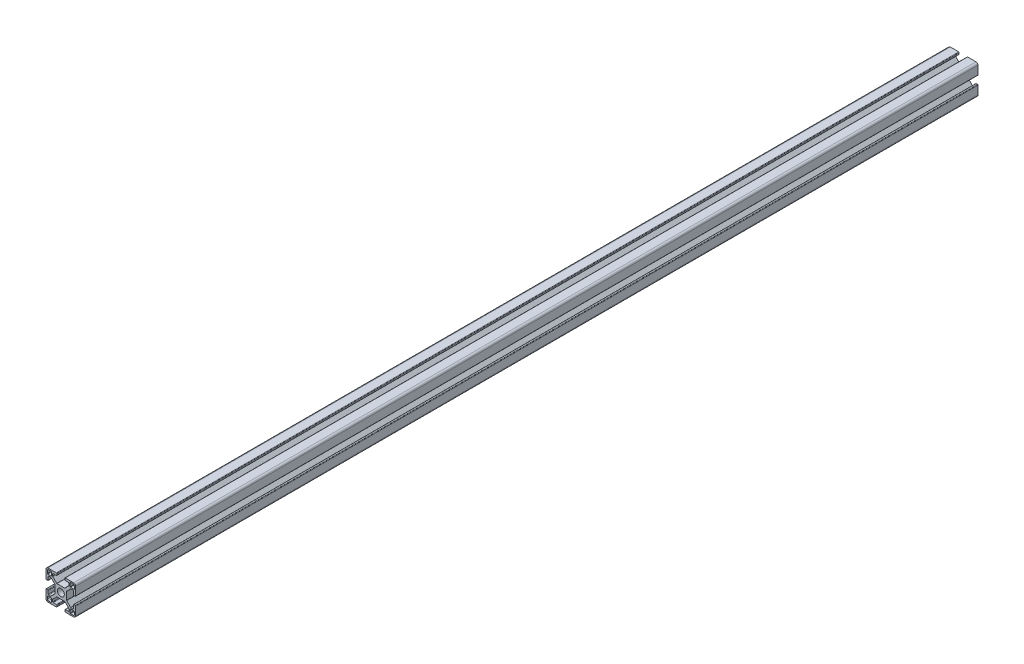
SolidWorks part; units mm, degrees
ref_plane "Front Plane" through (0, 0, 0) normal (0, 0, 1) x (1, 0, 0)
ref_plane "Top Plane" through (0, 0, 0) normal (0, 1, 0) x (1, 0, 0)
ref_plane "Right Plane" through (0, 0, 0) normal (1, 0, 0) x (0, 0, -1)
sketch "Sketch1" plane through (0, 0, 0) normal (0, 0, 1) x (1, 0, 0)
  line L0 (3.9799, -2.4733) -> (3.1981, -1.4942) construction
  line L1 (1.4942, -3.1981) -> (2.4733, -3.9799) construction
  line L2 (-2.4733, -3.9799) -> (-1.4942, -3.1981) construction
  line L3 (-3.1981, -1.4942) -> (-3.9799, -2.4733) construction
  line L4 (-3.9799, 2.4733) -> (-3.1981, 1.4942) construction
  line L5 (-1.4942, 3.1981) -> (-2.4733, 3.9799) construction
  line L6 (2.4733, 3.9799) -> (1.4942, 3.1981) construction
  line L7 (3.1981, 1.4942) -> (3.9799, 2.4733) construction
  line L8 (-12.6999, -13.6999) -> (-9.881, -13.6999)
  line L9 (-13.6999, -9.881) -> (-13.6999, -12.6999)
  line L10 (-9.88, -9.5) -> (-13.3189, -9.5)
  line L11 (-9.5, -13.3189) -> (-9.5, -9.88)
  line L12 (13.6999, -12.6999) -> (13.6999, -9.881)
  line L13 (9.881, -13.6999) -> (12.6999, -13.6999)
  line L14 (9.5, -9.88) -> (9.5, -13.3189)
  line L15 (13.3189, -9.5) -> (9.88, -9.5)
  line L16 (9.88, 9.5) -> (13.3189, 9.5)
  line L17 (9.5, 13.3189) -> (9.5, 9.88)
  line L18 (12.6999, 13.6999) -> (9.881, 13.6999)
  line L19 (13.6999, 9.881) -> (13.6999, 12.6999)
  line L20 (-13.6999, 12.6999) -> (-13.6999, 9.881)
  line L21 (-9.881, 13.6999) -> (-12.6999, 13.6999)
  line L22 (-9.5, 9.88) -> (-9.5, 13.3189)
  line L23 (-13.3189, 9.5) -> (-9.88, 9.5)
  line L24 (14.4999, -4) -> (13.2425, -4)
  line L25 (12.7425, -4.5) -> (12.7425, -7.7325)
  line L26 (12.2428, -8.25) -> (10.2602, -8.25)
  line L27 (9.9066, -8.1035) -> (5.9811, -4.178)
  line L28 (5.8347, -3.8245) -> (5.8347, -1.0125)
  line L29 (5.8347, -1.0125) -> (5.3247, -0.0625) construction
  line L30 (5.3247, -0.0625) -> (5.8347, 0.8875) construction
  line L31 (5.8347, 0.8875) -> (5.8347, 3.8245)
  line L32 (5.9811, 4.178) -> (9.9066, 8.1035)
  line L33 (10.2602, 8.25) -> (12.2428, 8.25)
  line L34 (12.7425, 7.7325) -> (12.7425, 4.5)
  line L35 (13.2425, 4) -> (14.4999, 4)
  line L36 (14.9999, 4.5) -> (14.9999, 12.9999)
  line L37 (12.9999, 14.9999) -> (4.5, 14.9999)
  line L38 (4, 14.4999) -> (4, 13.2425)
  line L39 (4.5, 12.7425) -> (7.7325, 12.7425)
  line L40 (8.25, 12.2428) -> (8.25, 10.2602)
  line L41 (8.1035, 9.9066) -> (4.178, 5.9811)
  line L42 (3.8245, 5.8347) -> (0.95, 5.8347)
  line L43 (0.95, 5.8347) -> (0, 5.3247) construction
  line L44 (0, 5.3247) -> (-0.95, 5.8347) construction
  line L45 (-0.95, 5.8347) -> (-3.8245, 5.8347)
  line L46 (-4.178, 5.9811) -> (-8.1035, 9.9066)
  line L47 (-8.25, 10.2602) -> (-8.25, 12.2428)
  line L48 (-7.7325, 12.7425) -> (-4.5, 12.7425)
  line L49 (-4, 13.2425) -> (-4, 14.4999)
  line L50 (-4.5, 14.9999) -> (-12.9999, 14.9999)
  line L51 (-14.9999, 12.9999) -> (-14.9999, 4.5)
  line L52 (-14.4999, 4) -> (-13.2425, 4)
  line L53 (-12.7425, 4.5) -> (-12.7425, 7.7325)
  line L54 (-12.2428, 8.25) -> (-10.2602, 8.25)
  line L55 (-9.9066, 8.1035) -> (-5.9811, 4.178)
  line L56 (-5.8347, 3.8245) -> (-5.8347, 0.8875)
  line L57 (-5.8347, 0.8875) -> (-5.3247, -0.0625) construction
  line L58 (-5.3247, -0.0625) -> (-5.8347, -1.0125) construction
  line L59 (-5.8347, -1.0125) -> (-5.8347, -3.8245)
  line L60 (-5.9811, -4.178) -> (-9.9066, -8.1035)
  line L61 (-10.2602, -8.25) -> (-12.2428, -8.25)
  line L62 (-12.7425, -7.7325) -> (-12.7425, -4.5)
  line L63 (-13.2425, -4) -> (-14.4999, -4)
  line L64 (-14.9999, -4.5) -> (-14.9999, -12.9999)
  line L65 (-12.9999, -14.9999) -> (-4.5, -14.9999)
  line L66 (-4, -14.4999) -> (-4, -13.2425)
  line L67 (-4.5, -12.7425) -> (-7.7325, -12.7425)
  line L68 (-8.25, -12.2428) -> (-8.25, -10.2602)
  line L69 (-8.1035, -9.9066) -> (-4.178, -5.9811)
  line L70 (-3.8245, -5.8347) -> (-0.95, -5.8347)
  line L71 (-0.95, -5.8347) -> (0, -5.3247) construction
  line L72 (0, -5.3247) -> (0.95, -5.8347) construction
  line L73 (0.95, -5.8347) -> (3.8245, -5.8347)
  line L74 (4.178, -5.9811) -> (8.1035, -9.9066)
  line L75 (8.25, -10.2602) -> (8.25, -12.2428)
  line L76 (7.7325, -12.7425) -> (4.5, -12.7425)
  line L77 (4, -13.2425) -> (4, -14.4999)
  line L78 (4.5, -14.9999) -> (12.9999, -14.9999)
  line L79 (14.9999, -12.9999) -> (14.9999, -4.5)
  line L80 (-5.8347, -1.0125) -> (-5.8347, 0.8875)
  line L81 (-0.95, 5.8347) -> (0.95, 5.8347)
  line L82 (5.8347, 0.8875) -> (5.8347, -1.0125)
  line L83 (-0.95, -5.8347) -> (0.95, -5.8347)
  arc A0 (2.4733, -3.9799) -> (3.9799, -2.4733) centre (3.1422, -3.1422) ccw construction
  arc A1 (-1.4942, -3.1981) -> (1.4942, -3.1981) centre (0, 0) ccw construction
  arc A2 (-3.9799, -2.4733) -> (-2.4733, -3.9799) centre (-3.1422, -3.1422) ccw construction
  arc A3 (-3.1981, 1.4942) -> (-3.1981, -1.4942) centre (0, 0) ccw construction
  arc A4 (-2.4733, 3.9799) -> (-3.9799, 2.4733) centre (-3.1422, 3.1422) ccw construction
  arc A5 (1.4942, 3.1981) -> (-1.4942, 3.1981) centre (0, 0) ccw construction
  arc A6 (3.9799, 2.4733) -> (2.4733, 3.9799) centre (3.1422, 3.1422) ccw construction
  arc A7 (3.1981, -1.4942) -> (3.1981, 1.4942) centre (0, 0) ccw construction
  arc A8 (-13.6999, -12.6999) -> (-12.6999, -13.6999) centre (-12.6999, -12.6999) ccw
  arc A9 (-13.3189, -9.5) -> (-13.6999, -9.881) centre (-13.3189, -9.881) ccw
  arc A10 (-9.5, -9.88) -> (-9.88, -9.5) centre (-9.88, -9.88) ccw
  arc A11 (-9.881, -13.6999) -> (-9.5, -13.3189) centre (-9.881, -13.3189) ccw
  arc A12 (12.6999, -13.6999) -> (13.6999, -12.6999) centre (12.6999, -12.6999) ccw
  arc A13 (9.5, -13.3189) -> (9.881, -13.6999) centre (9.881, -13.3189) ccw
  arc A14 (9.88, -9.5) -> (9.5, -9.88) centre (9.88, -9.88) ccw
  arc A15 (13.6999, -9.881) -> (13.3189, -9.5) centre (13.3189, -9.881) ccw
  arc A16 (9.5, 9.88) -> (9.88, 9.5) centre (9.88, 9.88) ccw
  arc A17 (9.881, 13.6999) -> (9.5, 13.3189) centre (9.881, 13.3189) ccw
  arc A18 (13.6999, 12.6999) -> (12.6999, 13.6999) centre (12.6999, 12.6999) ccw
  arc A19 (13.3189, 9.5) -> (13.6999, 9.881) centre (13.3189, 9.881) ccw
  arc A20 (14.9999, -4.5) -> (14.4999, -4) centre (14.4999, -4.5) ccw
  arc A21 (13.2425, -4) -> (12.7425, -4.5) centre (13.2425, -4.5) ccw
  arc A22 (12.2428, -8.25) -> (12.7425, -7.7325) centre (12.2428, -7.75) ccw
  arc A23 (9.9066, -8.1035) -> (10.2602, -8.25) centre (10.2602, -7.75) ccw
  arc A24 (5.8347, -3.8245) -> (5.9811, -4.178) centre (6.3347, -3.8245) ccw
  arc A25 (5.9811, 4.178) -> (5.8347, 3.8245) centre (6.3347, 3.8245) ccw
  arc A26 (10.2602, 8.25) -> (9.9066, 8.1035) centre (10.2602, 7.75) ccw
  arc A27 (12.7425, 7.7325) -> (12.2428, 8.25) centre (12.2428, 7.75) ccw
  arc A28 (12.7425, 4.5) -> (13.2425, 4) centre (13.2425, 4.5) ccw
  arc A29 (14.4999, 4) -> (14.9999, 4.5) centre (14.4999, 4.5) ccw
  arc A30 (14.9999, 12.9999) -> (12.9999, 14.9999) centre (12.9999, 12.9999) ccw
  arc A31 (4.5, 14.9999) -> (4, 14.4999) centre (4.5, 14.4999) ccw
  arc A32 (4, 13.2425) -> (4.5, 12.7425) centre (4.5, 13.2425) ccw
  arc A33 (8.25, 12.2428) -> (7.7325, 12.7425) centre (7.75, 12.2428) ccw
  arc A34 (8.1035, 9.9066) -> (8.25, 10.2602) centre (7.75, 10.2602) ccw
  arc A35 (3.8245, 5.8347) -> (4.178, 5.9811) centre (3.8245, 6.3347) ccw
  arc A36 (-4.178, 5.9811) -> (-3.8245, 5.8347) centre (-3.8245, 6.3347) ccw
  arc A37 (-8.25, 10.2602) -> (-8.1035, 9.9066) centre (-7.75, 10.2602) ccw
  arc A38 (-7.7325, 12.7425) -> (-8.25, 12.2428) centre (-7.75, 12.2428) ccw
  arc A39 (-4.5, 12.7425) -> (-4, 13.2425) centre (-4.5, 13.2425) ccw
  arc A40 (-4, 14.4999) -> (-4.5, 14.9999) centre (-4.5, 14.4999) ccw
  arc A41 (-12.9999, 14.9999) -> (-14.9999, 12.9999) centre (-12.9999, 12.9999) ccw
  arc A42 (-14.9999, 4.5) -> (-14.4999, 4) centre (-14.4999, 4.5) ccw
  arc A43 (-13.2425, 4) -> (-12.7425, 4.5) centre (-13.2425, 4.5) ccw
  arc A44 (-12.2428, 8.25) -> (-12.7425, 7.7325) centre (-12.2428, 7.75) ccw
  arc A45 (-9.9066, 8.1035) -> (-10.2602, 8.25) centre (-10.2602, 7.75) ccw
  arc A46 (-5.8347, 3.8245) -> (-5.9811, 4.178) centre (-6.3347, 3.8245) ccw
  arc A47 (-5.9811, -4.178) -> (-5.8347, -3.8245) centre (-6.3347, -3.8245) ccw
  arc A48 (-10.2602, -8.25) -> (-9.9066, -8.1035) centre (-10.2602, -7.75) ccw
  arc A49 (-12.7425, -7.7325) -> (-12.2428, -8.25) centre (-12.2428, -7.75) ccw
  arc A50 (-12.7425, -4.5) -> (-13.2425, -4) centre (-13.2425, -4.5) ccw
  arc A51 (-14.4999, -4) -> (-14.9999, -4.5) centre (-14.4999, -4.5) ccw
  arc A52 (-14.9999, -12.9999) -> (-12.9999, -14.9999) centre (-12.9999, -12.9999) ccw
  arc A53 (-4.5, -14.9999) -> (-4, -14.4999) centre (-4.5, -14.4999) ccw
  arc A54 (-4, -13.2425) -> (-4.5, -12.7425) centre (-4.5, -13.2425) ccw
  arc A55 (-8.25, -12.2428) -> (-7.7325, -12.7425) centre (-7.75, -12.2428) ccw
  arc A56 (-8.1035, -9.9066) -> (-8.25, -10.2602) centre (-7.75, -10.2602) ccw
  arc A57 (-3.8245, -5.8347) -> (-4.178, -5.9811) centre (-3.8245, -6.3347) ccw
  arc A58 (4.178, -5.9811) -> (3.8245, -5.8347) centre (3.8245, -6.3347) ccw
  arc A59 (8.25, -10.2602) -> (8.1035, -9.9066) centre (7.75, -10.2602) ccw
  arc A60 (7.7325, -12.7425) -> (8.25, -12.2428) centre (7.75, -12.2428) ccw
  arc A61 (4.5, -12.7425) -> (4, -13.2425) centre (4.5, -13.2425) ccw
  arc A62 (4, -14.4999) -> (4.5, -14.9999) centre (4.5, -14.4999) ccw
  arc A63 (12.9999, -14.9999) -> (14.9999, -12.9999) centre (12.9999, -12.9999) ccw
  arc A64 (-12.6999, 13.6999) -> (-13.6999, 12.6999) centre (-12.6999, 12.6999) ccw
  arc A65 (-9.5, 13.3189) -> (-9.881, 13.6999) centre (-9.881, 13.3189) ccw
  arc A66 (-9.88, 9.5) -> (-9.5, 9.88) centre (-9.88, 9.88) ccw
  arc A67 (-13.6999, 9.881) -> (-13.3189, 9.5) centre (-13.3189, 9.881) ccw
  circle A68 centre (0, 0) radius 3.53
extrude "Boss-Extrude1" add sketch "Sketch1" along normal mid plane 914.4
